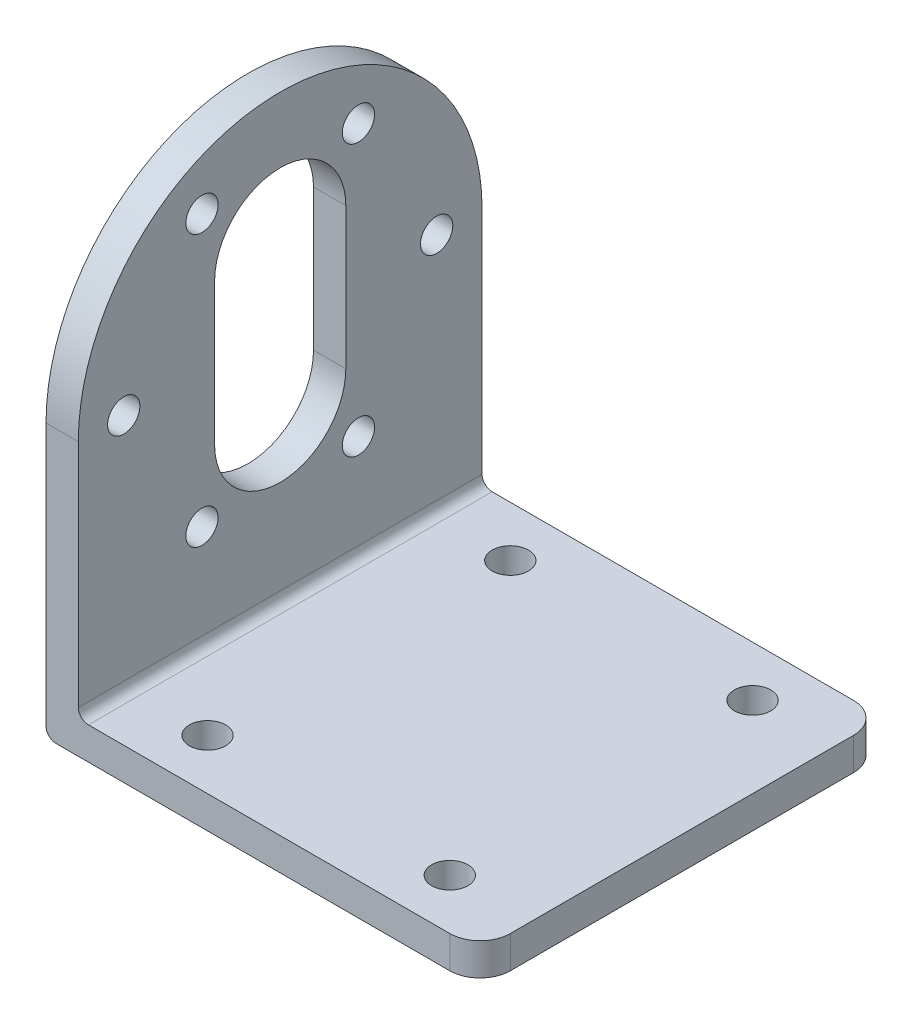
SolidWorks part; units mm, degrees
ref_plane "前视基准面" through (0, 0, 0) normal (0, 0, 1) x (1, 0, 0)
ref_plane "上视基准面" through (0, 0, 0) normal (0, 1, 0) x (1, 0, 0)
ref_plane "右视基准面" through (0, 0, 0) normal (1, 0, 0) x (0, 0, -1)
sketch "草图1" plane through (0, 0, 0) normal (0, 1, 0) x (1, 0, 0)
  line L1 (-21.5, -20) -> (21.5, -20)
  line L2 (-21.5, -20) -> (-21.5, 20)
  line L3 (-21.5, 20) -> (21.5, 20)
  line L4 (21.5, -20) -> (21.5, 20)
  line L5 (-21.5, -20) -> (21.5, 20) construction
  line L6 (-21.5, 20) -> (21.5, -20) construction
  point P0 (0, 0)
  dimension "D1" = 40
  dimension "D2" = 43
extrude "凸台-拉伸1" add sketch "草图1" along normal blind 3.2
sketch "草图2" plane through (0, 3.2, 0) normal (0, 1, 0) x (1, 0, 0)
  line L0 (21.5, 20) -> (-21.5, 20) construction
  line L1 (-21.5, -20) -> (-18.3, -20)
  line L2 (-21.5, -20) -> (-21.5, 20)
  line L3 (-21.5, 20) -> (-18.3, 20)
  line L4 (-18.3, -20) -> (-18.3, 20)
  dimension "D1" = 3.2
extrude "凸台-拉伸2" add sketch "草图2" along normal blind 23.8
sketch "草图3" plane through (-18.3, 0, 0) normal (1, 0, 0) x (0, 0, -1)
  line L0 (-20, 27) -> (20, 27) construction
  line L1 (-20, 27) -> (20, 27)
  arc A0 (20, 27) -> (-20, 27) centre (0, 27) ccw
extrude "凸台-拉伸3" add sketch "草图3" against normal up to surface (3.2 mm away) up to face at (-21.5, 13.5, 0)
sketch "草图4" plane through (0, 3.2, 0) normal (0, 1, 0) x (1, 0, 0)
  line L0 (21.5, -20) -> (21.5, 20) construction
  circle A0 centre (13.5, 15) radius 1.8
  circle A1 centre (-10.5, 15) radius 1.8
  circle A2 centre (-10.5, -15) radius 1.8
  circle A3 centre (13.5, -15) radius 1.8
  point P4 (21.5, 0)
  dimension "D1" = 3.6
  dimension "D2" = 15
  dimension "D3" = 8
  dimension "D4" = 2
  dimension "D5" = 2
extrude "切除-拉伸1" cut sketch "草图4" against normal through all
fillet "圆角1" radius 3 2 edges at (21.5, 1.6, 20) (21.5, 1.6, -20)
sketch "草图5" plane through (-18.3, 0, 0) normal (1, 0, 0) x (0, 0, -1)
  line L0 (0, 34) -> (0, 20) construction
  line L1 (6.5, 34) -> (6.5, 20)
  line L2 (-6.5, 34) -> (-6.5, 20)
  line L3 (-7.75, 40.4234) -> (0, 27) construction
  circle A0 centre (0, 27) radius 15.5 construction
  arc A1 (6.5, 34) -> (-6.5, 34) centre (0, 34) ccw
  arc A2 (-6.5, 20) -> (6.5, 20) centre (0, 20) ccw
  circle A3 centre (-7.75, 40.4234) radius 1.6
  circle A4 centre (7.75, 40.4234) radius 1.6
  circle A5 centre (15.5, 27) radius 1.6
  circle A6 centre (7.75, 13.5766) radius 1.6
  circle A7 centre (-7.75, 13.5766) radius 1.6
  circle A8 centre (-15.5, 27) radius 1.6
  circle A9 centre (-8.5, 27) radius 1.6 construction
  circle A10 centre (8.5, 27) radius 1.6 construction
  point P6 (0, 27)
  point P12 (6.5, 27)
  point P27 (4.9796, 24.125)
  point P41 (-4.9796, 24.125)
  point P42 (0, 27)
  dimension "D2" = 6.5
  dimension "D3" = 31
  dimension "D4" = 30
  dimension "D5" = 3.2
  dimension "D7" = 8.5
  dimension "D1" = 14
  dimension "D8" = 17
  dimension "D6" = 6
extrude "切除-拉伸2" cut sketch "草图5" against normal up to next
fillet "圆角2" radius 1 2 edges at (-18.3, 3.2, 0) (-21.5, 0, 0)
equation "\"D1@凸台-拉伸2\"=25.50"
